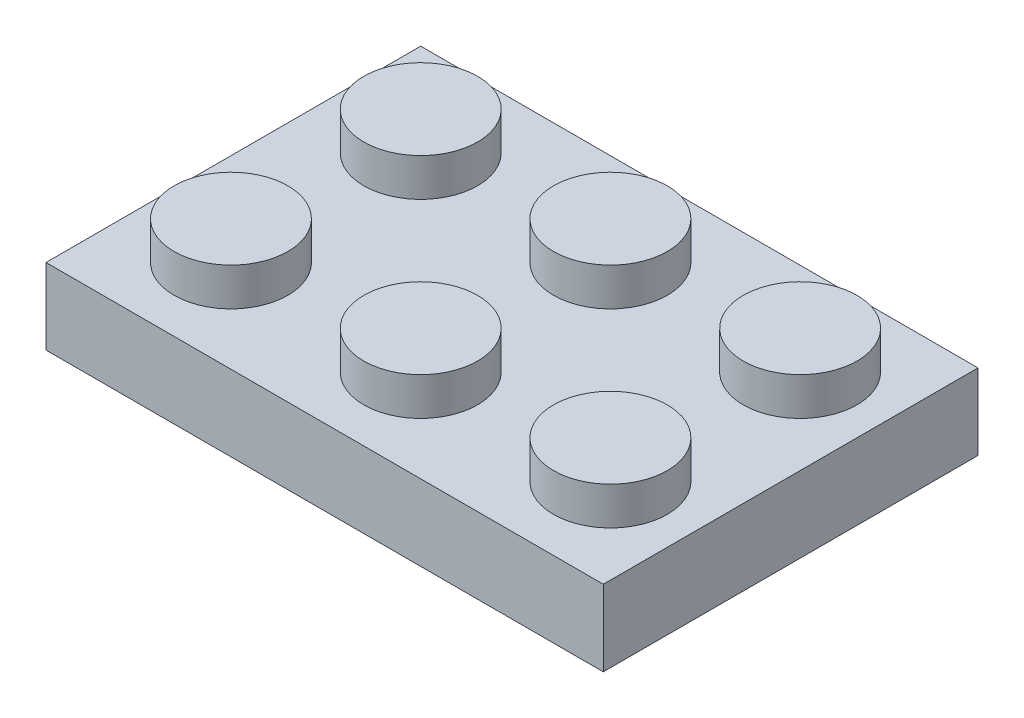
SolidWorks part; units mm, degrees
material "ABS"
ref_plane "Front Plane" through (0, 0, 0) normal (0, 0, 1) x (1, 0, 0)
ref_plane "Top Plane" through (0, 0, 0) normal (0, 1, 0) x (1, 0, 0)
ref_plane "Right Plane" through (0, 0, 0) normal (1, 0, 0) x (0, 0, -1)
sketch "Sketch1" plane through (0, 0, 0) normal (0, 0, 1) x (1, 0, 0)
  line L1 (0, 0) -> (23.5, 0)
  line L2 (0, 0) -> (0, 3.2)
  line L3 (0, 3.2) -> (23.5, 3.2)
  line L4 (23.5, 0) -> (23.5, 3.2)
  line L5 (0, 0) -> (23.5, 3.2) construction
  line L6 (0, 3.2) -> (23.5, 0) construction
  point P4 (11.75, 1.6)
  dimension "D1" = 23.5
  dimension "D2" = 3.2
extrude "Boss-Extrude1" add sketch "Sketch1" against normal blind 15.8
sketch "Sketch2" plane through (0, 3.2, 0) normal (0, 1, 0) x (1, 0, 0)
  line L0 (23.5, 0) -> (0, 0) construction
  circle A0 centre (3.9, 3.9) radius 2.4
  dimension "D1" = 4.8
  dimension "D2" = 3.9
  dimension "D3" = 3.9
extrude "Boss-Extrude2" add sketch "Sketch2" along normal blind 1.6
pattern_linear "LPattern1" count 2 spacing 8 along (0, 0, -1) count 4 spacing 8 along (1, 0, 0) of "Boss-Extrude2"
shell "Shell1" thickness 1.2
sketch "Sketch4" plane through (0, 2, 0) normal (0, -1, 0) x (1, 0, 0)
  line L0 (0, -15.8) -> (0, 0) construction
  line L1 (0, 0) -> (23.5, 0) construction
  circle A0 centre (7.9, -7.9) radius 3.25
  circle A1 centre (7.9, -7.9) radius 2.4
  dimension "D1" = 4.8
  dimension "D2" = 6.5
  dimension "D3" = 7.9
  dimension "D4" = 7.9
extrude "Boss-Extrude3" add sketch "Sketch4" along normal offset from surface (1.8 mm away) 0.2 up to face at (11.75, 0, -7.9)
pattern_linear "LPattern2" count 2 spacing 8 along (1, 0, 0) of "Boss-Extrude3"
